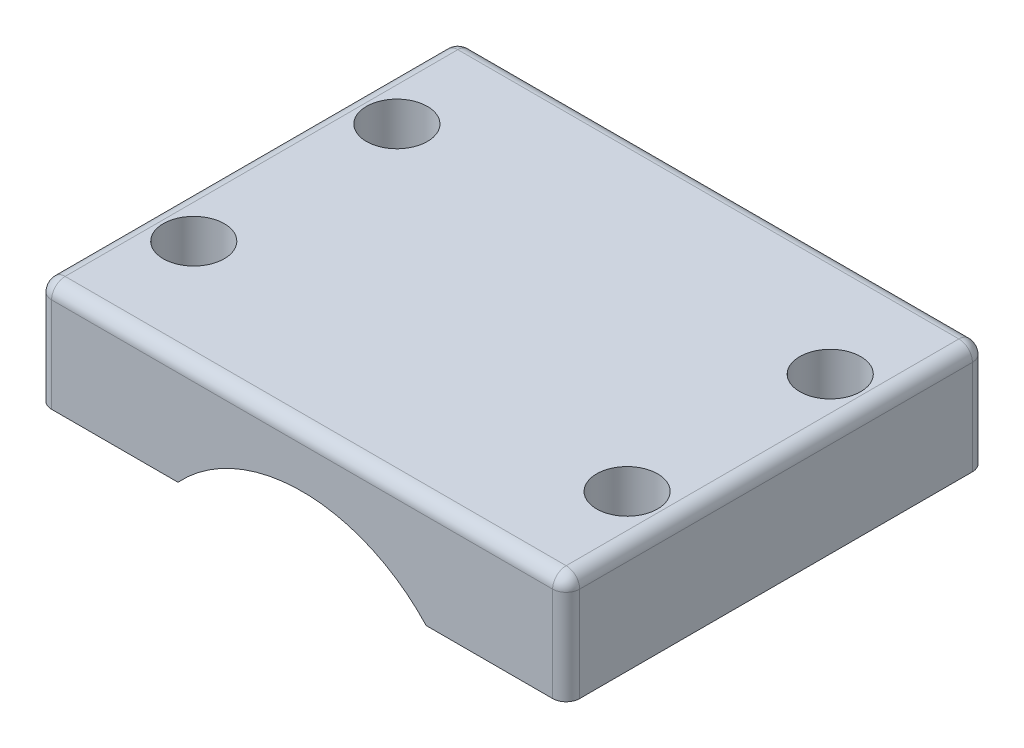
SolidWorks part; units mm, degrees
ref_plane "Front Plane" through (0, 0, 0) normal (0, 0, 1) x (1, 0, 0)
ref_plane "Top Plane" through (0, 0, 0) normal (0, 1, 0) x (1, 0, 0)
ref_plane "Right Plane" through (0, 0, 0) normal (1, 0, 0) x (0, 0, -1)
sketch "Sketch1" plane through (0, 0, 0) normal (0, 1, 0) x (1, 0, 0)
  line L0 (0, 15.5) -> (39, 15.5) construction
  line L1 (0, 31) -> (39, 31)
  line L2 (0, 31) -> (0, 0)
  line L3 (0, 0) -> (39, 0)
  line L4 (39, 31) -> (39, 0)
  line L5 (19.5, 0) -> (19.5, 31) construction
  circle A0 centre (35.5, 23) radius 2.25
  circle A1 centre (35.5, 8) radius 2.25
  circle A2 centre (3.5, 23) radius 2.25
  circle A3 centre (3.5, 8) radius 2.25
  dimension "D3" = 4.5
  dimension "D1" = 39
  dimension "D2" = 31
  dimension "D4" = 8
  dimension "D5" = 3.5
extrude "Boss-Extrude1" add sketch "Sketch1" along normal blind 8
fillet "Fillet2" radius 1 8 edges at (19.5, 8, -31) (0, 8, -15.5) (39, 8, -15.5) (19.5, 8, 0) (0, 4, 0) (39, 4, 0) (39, 4, -31) (0, 4, -31)
sketch "Sketch2" plane through (0, 0, 0) normal (0, 0, 1) x (1, 0, 0)
  line L0 (1, 8) -> (38, 8) construction
  line L4 (1, 0) -> (38, 0) construction
  line L5 (10.3348, 0) -> (-5.5, 0)
  line L6 (44.5, 0) -> (28.6652, 0)
  line L7 (44.5, 0) -> (44.5, -10)
  line L8 (44.5, -10) -> (-5.5, -10)
  line L9 (-5.5, 0) -> (-5.5, -10)
  arc A0 (10.3348, 0) -> (28.6652, 0) centre (19.5, -8.5) cw
  point P6 (19.5, 8)
  point P7 (19.5, 4)
  point P16 (19.5, 0)
  dimension "D1" = 12.5
  dimension "D2" = 4
  dimension "D3" = 50
  dimension "D4" = 10
extrude "Cut-Extrude1" cut sketch "Sketch2" against normal up to surface (31 mm away) up to face at (19.5, 3.5, -31)
